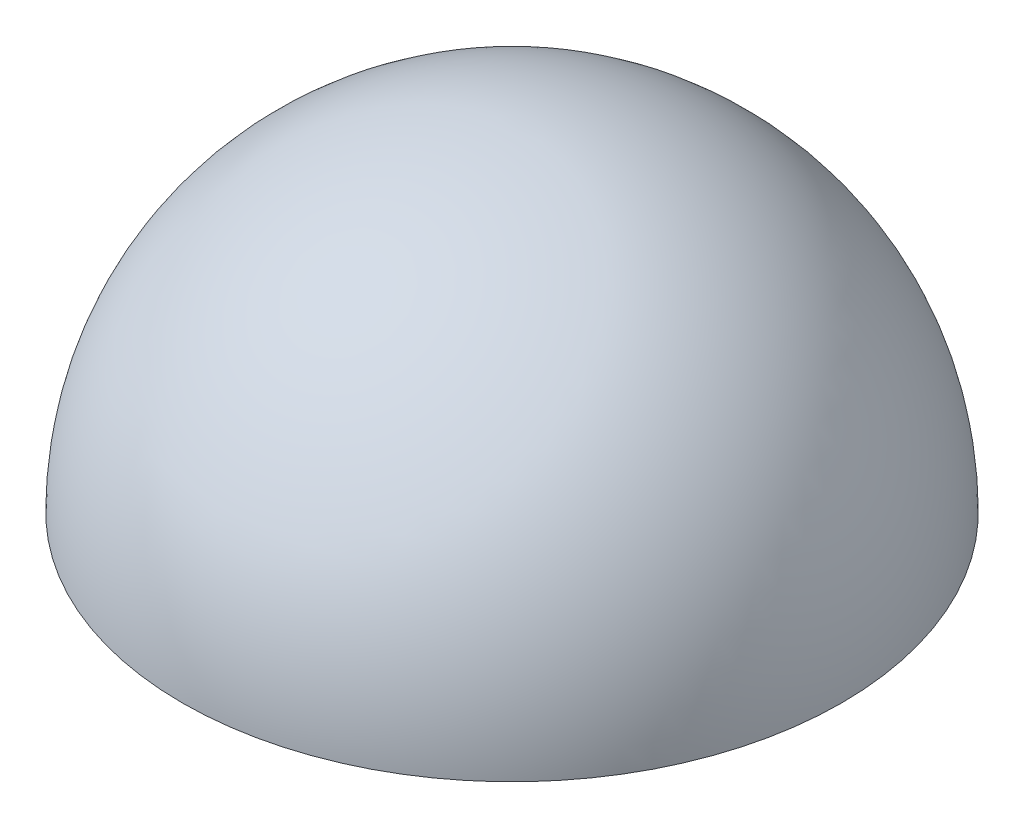
SolidWorks part; units mm, degrees
material "Delrin 2700 NC010, Low Viscosity Acetal Copolymer (SS)"
ref_plane "Front Plane" through (0, 0, 0) normal (0, 0, 1) x (1, 0, 0)
ref_plane "Top Plane" through (0, 0, 0) normal (0, 1, 0) x (1, 0, 0)
ref_plane "Right Plane" through (0, 0, 0) normal (1, 0, 0) x (0, 0, -1)
sketch "Sketch1" plane through (0, 0, 0) normal (1, 0, 0) x (0, 0, -1)
  line L0 (0, 0) -> (0, 12.7)
  line L1 (0, 0) -> (-12.7, 0)
  arc A0 (0, 12.7) -> (-12.7, 0) centre (0, 0) ccw
  dimension "D1" = 12.7
ref_axis "Axis1" through (0, 0, 0) along (0, 1, 0)
revolve "Revolve1" add sketch "Sketch1" angle 360 about axis through (0, 0, 0) along (0, 1, 0)
